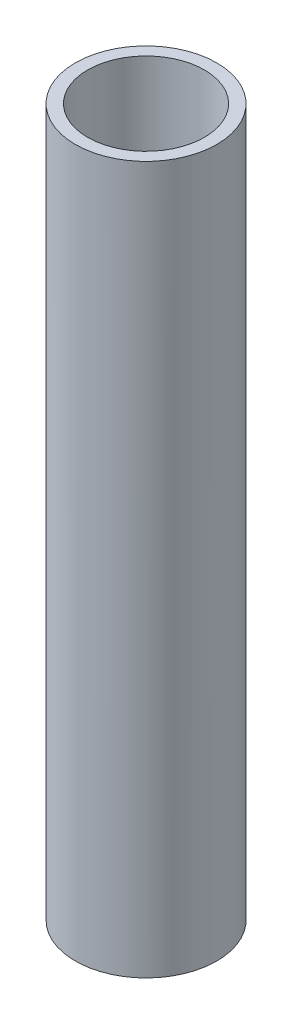
SolidWorks part; units mm, degrees
ref_plane "Front Plane" through (0, 0, 0) normal (0, 0, 1) x (1, 0, 0)
ref_plane "Top Plane" through (0, 0, 0) normal (0, 1, 0) x (1, 0, 0)
ref_plane "Right Plane" through (0, 0, 0) normal (1, 0, 0) x (0, 0, -1)
sketch "Sketch1" plane through (0, 0, 0) normal (0, 1, 0) x (1, 0, 0)
  circle A0 centre (0, 0) radius 12.065
  circle A1 centre (0, 0) radius 14.605
  dimension "D1" = 24.13
  dimension "D2" = 2.54
extrude "Boss-Extrude1" add sketch "Sketch1" along normal blind 146.05
sketch "Sketch2" plane through (0, 0, 0) normal (0, 0, 1) x (1, 0, 0)
  line L0 (-14.605, 0) -> (14.605, 0) construction
  line L1 (-1.778, 0) -> (1.778, 0)
  line L2 (-1.778, 0) -> (-1.778, 25.4)
  line L3 (-1.778, 25.4) -> (1.778, 25.4)
  line L4 (1.778, 0) -> (1.778, 25.4)
  point P6 (0, 25.4)
  dimension "D1" = 3.556
  dimension "D2" = 25.4
extrude "Cut-Extrude1" cut sketch "Sketch2" against normal blind 25.4
